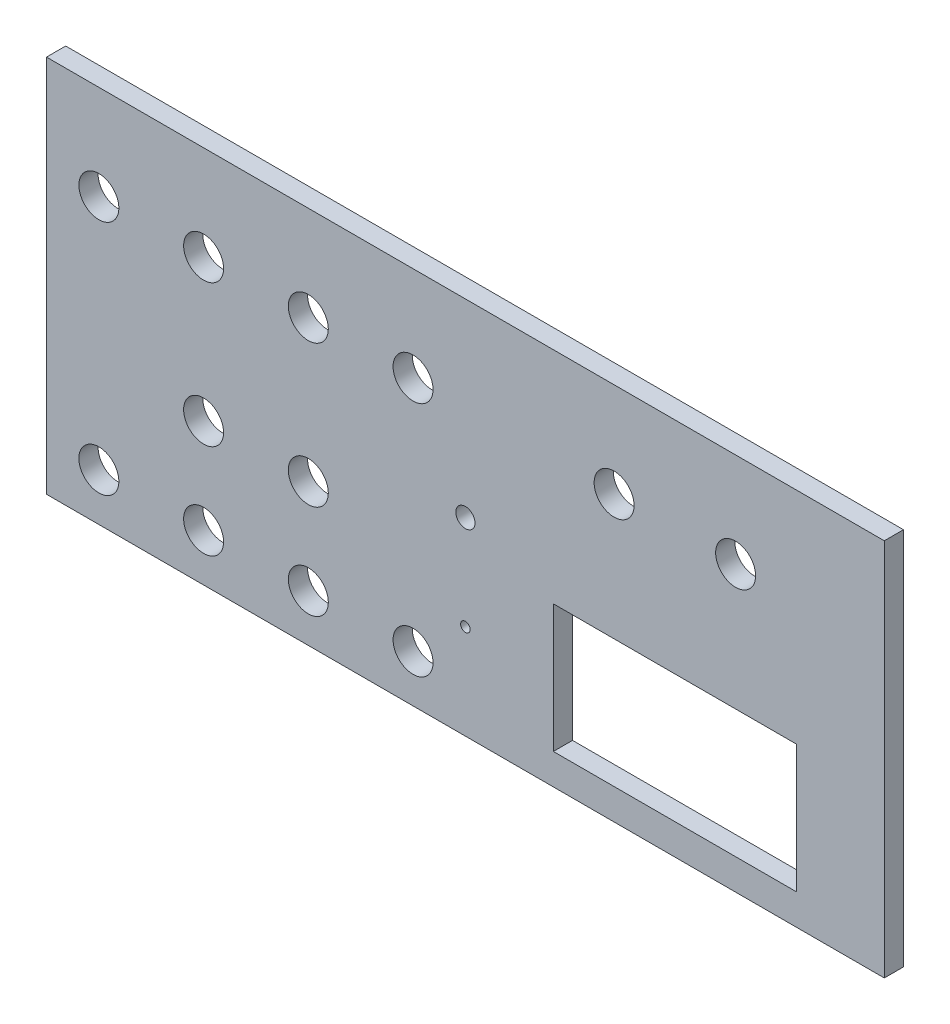
SolidWorks part; units mm, degrees
ref_plane "Plan de face" through (0, 0, 0) normal (0, 0, 1) x (1, 0, 0)
ref_plane "Plan de dessus" through (0, 0, 0) normal (0, 1, 0) x (1, 0, 0)
ref_plane "Plan de droite" through (0, 0, 0) normal (1, 0, 0) x (0, 0, -1)
sketch "Esquisse1" plane through (0, 0, 0) normal (0, 0, 1) x (1, 0, 0)
  line L0 (0, -112.4149) -> (-250, -112.4149) construction
  line L1 (6, 6) -> (-256, 6)
  line L2 (6, 6) -> (6, -112.4149)
  line L3 (6, -112.4149) -> (-256, -112.4149)
  line L4 (-256, 6) -> (-256, -112.4149)
extrude "Boss.-Extru.1" add sketch "Esquisse1" along normal blind 6
sketch "Esquisse2" plane through (0, 0, 6) normal (0, 0, 1) x (1, 0, 0)
  line L0 (6, -53.2075) -> (-256, -53.2075) construction
  line L1 (-21.5, -102.8112) -> (-97.5, -102.8112)
  line L2 (-21.5, -102.8112) -> (-21.5, -62.8112)
  line L3 (-21.5, -62.8112) -> (-97.5, -62.8112)
  line L4 (-97.5, -102.8112) -> (-97.5, -62.8112)
  line L5 (-125, 6) -> (-256, 6) construction
  line L6 (-125, -112.4149) -> (-256, -112.4149) construction
  line L7 (6, -112.4149) -> (6, 6) construction
  line L10 (-256, 6) -> (-256, -112.4149) construction
  line L11 (-125, 6) -> (-125, -53.2075) construction
  line L12 (6, 6) -> (-256, 6) construction
  line L13 (-125, -53.2075) -> (-125, -112.4149) construction
  line L14 (-256, -112.4149) -> (6, -112.4149) construction
  line L15 (-97.5, -82.8112) -> (-125, -82.8112) construction
  line L16 (-21.5, -82.8112) -> (6, -82.8112) construction
  line L17 (-125, -23.6037) -> (-78.5, -23.6037) construction
  line L18 (-40.5, -23.6037) -> (6, -23.6037) construction
  line L19 (-40.5, -23.6037) -> (-78.5, -23.6037) construction
  line L20 (-125, -112.4149) -> (-125, -82.8112) construction
  circle A0 centre (-40.5, -23.6037) radius 6.25
  circle A1 centre (-78.5, -23.6037) radius 6.25
  dimension "D3" = 12.5
  dimension "D1" = 76
  dimension "D2" = 40
  dimension "D4" = 38
extrude "Enlèv. mat.-Extru.1" cut sketch "Esquisse2" against normal up to next
sketch "Esquisse3" plane through (0, 0, 6) normal (0, 0, 1) x (1, 0, 0)
  line L0 (-125, -112.4149) -> (-125, 6) construction
  line L1 (-256, -112.4149) -> (6, -112.4149) construction
  line L2 (6, 6) -> (-256, 6) construction
  line L3 (-97.5, -82.8112) -> (-125, -82.8112) construction
  line L4 (-97.5, -62.8112) -> (-97.5, -102.8112) construction
  circle A0 centre (-125, -53.2075) radius 3
  circle A1 centre (-125, -82.8112) radius 1.5
  dimension "D1" = 3
  dimension "D2" = 6
extrude "Enlèv. mat.-Extru.2" cut sketch "Esquisse3" against normal up to next
sketch "Esquisse4" plane through (0, 0, 6) normal (0, 0, 1) x (1, 0, 0)
  line L0 (-125, -112.4149) -> (-125, -53.2075) construction
  line L1 (-256, -112.4149) -> (6, -112.4149) construction
  line L2 (-125, -53.2075) -> (-125, 6) construction
  line L3 (6, 6) -> (-256, 6) construction
  line L4 (-125, -53.2075) -> (-256, -53.2075) construction
  line L5 (-256, 6) -> (-256, -112.4149) construction
  line L6 (-190.5, -53.2075) -> (-190.5, -112.4149) construction
  line L7 (-190.5, -53.2075) -> (-190.5, 6) construction
  line L8 (-190.5, -23.6037) -> (-256, -23.6037) construction
  line L9 (-190.5, -23.6037) -> (-125, -23.6037) construction
  line L10 (-190.5, -82.8112) -> (-125, -82.8112) construction
  line L11 (-190.5, -82.8112) -> (-256, -82.8112) construction
  line L12 (-157.75, -82.8112) -> (-157.75, -112.4149) construction
  line L13 (-223.25, -82.8112) -> (-223.25, -112.4149) construction
  line L14 (-157.75, -23.6037) -> (-157.75, -53.2075) construction
  line L15 (-157.75, -23.6037) -> (-157.75, 6) construction
  line L16 (-223.25, -23.6037) -> (-223.25, -53.2075) construction
  line L17 (-223.25, -23.6037) -> (-223.25, 6) construction
  line L18 (-157.75, -82.8112) -> (-157.75, -53.2075) construction
  line L19 (-223.25, -82.8112) -> (-223.25, -53.2075) construction
  line L20 (-157.75, -68.0093) -> (-223.25, -68.0093) construction
  line L21 (-157.75, -38.4056) -> (-125, -38.4056) construction
  line L22 (-141.375, -38.4056) -> (-141.375, 6) construction
  line L23 (-157.75, -38.4056) -> (-190.5, -38.4056) construction
  line L24 (-174.125, -38.4056) -> (-174.125, -23.6037) construction
  line L25 (-174.125, -23.6037) -> (-174.125, 6) construction
  line L26 (-190.5, -38.4056) -> (-223.25, -38.4056) construction
  line L27 (-223.25, -38.4056) -> (-256, -38.4056) construction
  line L28 (-239.625, -38.4056) -> (-239.625, 6) construction
  line L29 (-206.875, -38.4056) -> (-206.875, 6) construction
  line L30 (-157.75, -97.613) -> (-125, -97.613) construction
  line L31 (-157.75, -97.613) -> (-190.5, -97.613) construction
  line L32 (-190.5, -97.613) -> (-223.25, -97.613) construction
  line L33 (-223.25, -97.613) -> (-256, -97.613) construction
  line L34 (-174.125, -53.2075) -> (-174.125, -82.8112) construction
  line L35 (-206.875, -82.8112) -> (-206.875, -53.2075) construction
  circle A0 centre (-141.375, -97.613) radius 6.25
  circle A1 centre (-174.125, -97.613) radius 6.25
  circle A2 centre (-206.875, -97.613) radius 6.25
  circle A3 centre (-239.625, -97.613) radius 6.25
  circle A4 centre (-174.125, -68.0093) radius 6.25
  circle A5 centre (-206.875, -68.0093) radius 6.25
  circle A6 centre (-141.375, -23.6037) radius 6.25
  circle A7 centre (-174.125, -23.6037) radius 6.25
  circle A8 centre (-206.875, -23.6037) radius 6.25
  circle A9 centre (-239.625, -23.6037) radius 6.25
  point P65 (-206.875, -68.0093)
  point P68 (-141.375, -23.6037)
  point P69 (-206.875, -23.6037)
  point P70 (-239.625, -23.6037)
  dimension "D1" = 12.5
extrude "Enlèv. mat.-Extru.3" cut sketch "Esquisse4" against normal up to next
